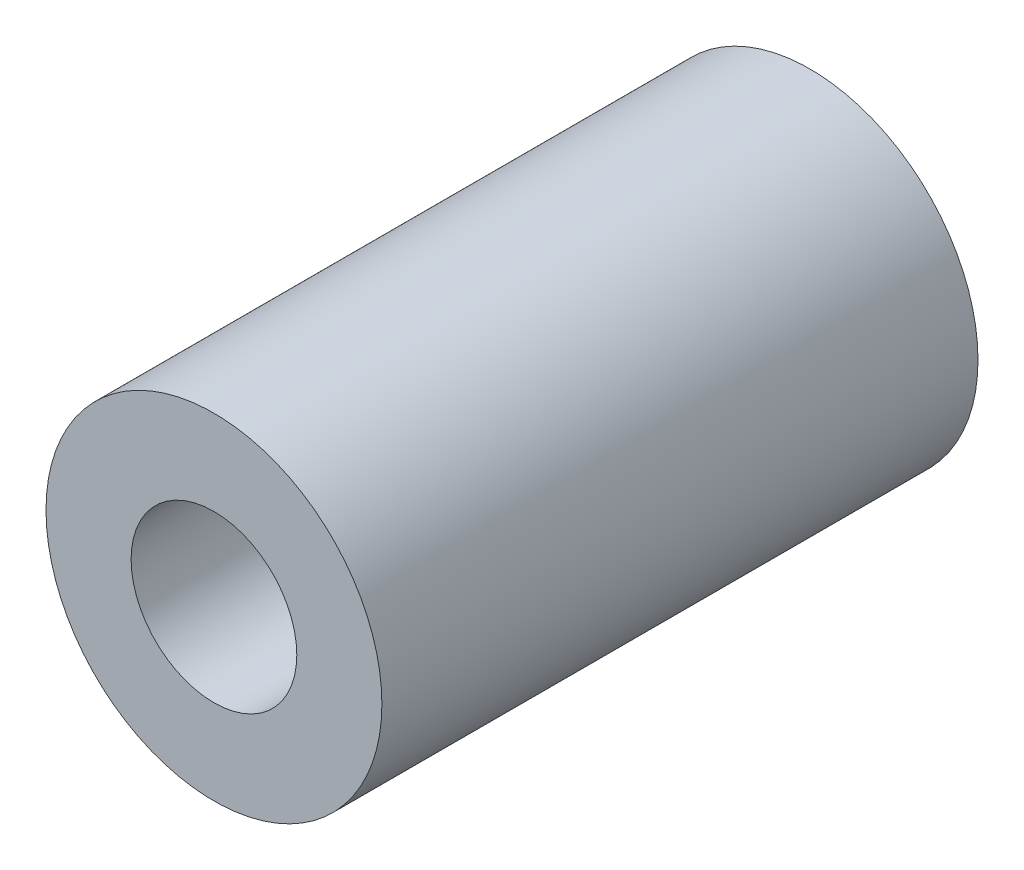
SolidWorks part; units mm, degrees
ref_plane "Front" through (0, 0, 0) normal (0, 0, 1) x (1, 0, 0)
ref_plane "Top" through (0, 0, 0) normal (0, 1, 0) x (1, 0, 0)
ref_plane "Right" through (0, 0, 0) normal (1, 0, 0) x (0, 0, -1)
sketch "Sketch1" plane through (0, 0, 0) normal (0, 0, 1) x (1, 0, 0)
  circle A9 centre (0, 0) radius 7.5
  dimension "D1" = 15
extrude "Boss-Extrude1" add sketch "Sketch1" along normal blind 26.62 contours A9
sketch "Sketch4" plane through (0, 0, 0) normal (0, 0, -1) x (-1, 0, 0)
  circle A0 centre (0, 0) radius 3.7
  dimension "D1" = 7.4
extrude "Cut-Extrude1" cut sketch "Sketch4" against normal blind 26.62 contours A0
